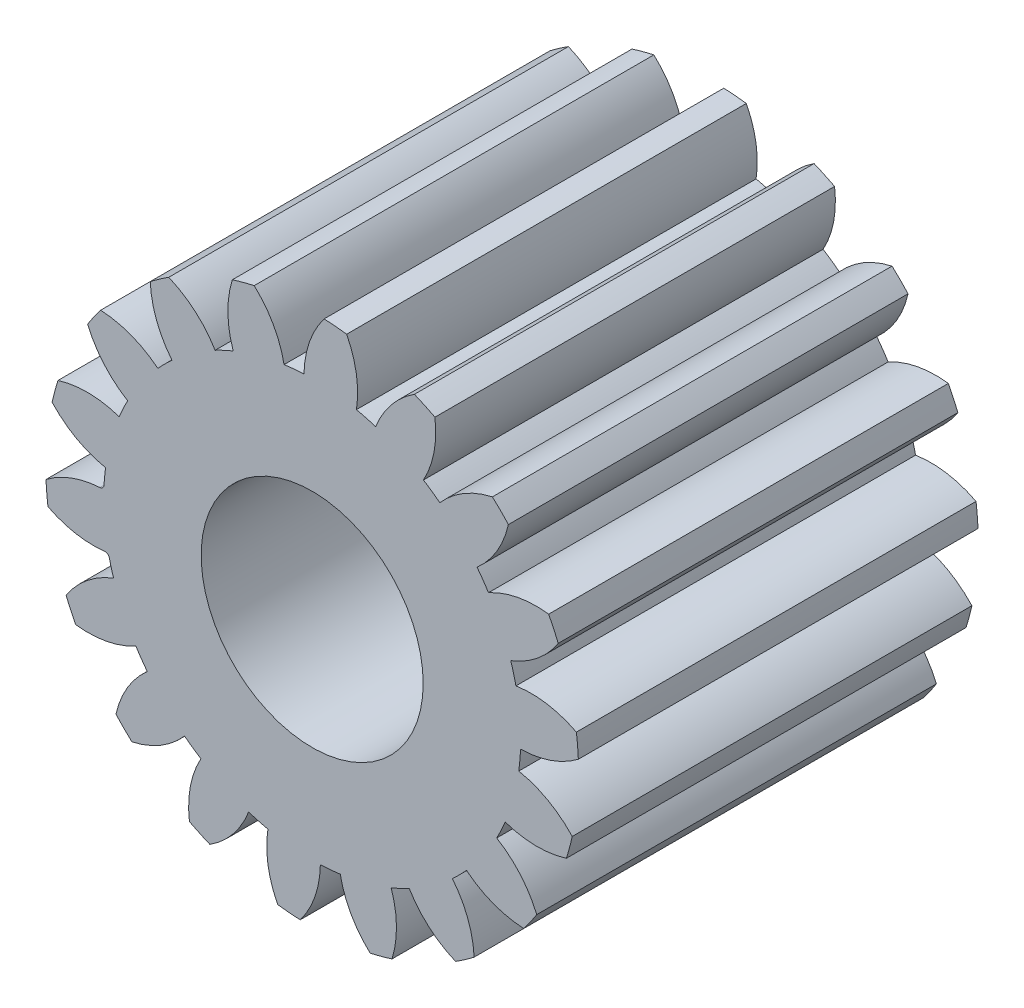
SolidWorks part; units mm, degrees
ref_plane "Front Plane" through (0, 0, 0) normal (0, 0, 1) x (1, 0, 0)
ref_plane "Top Plane" through (0, 0, 0) normal (0, 1, 0) x (1, 0, 0)
ref_plane "Right Plane" through (0, 0, 0) normal (1, 0, 0) x (0, 0, -1)
sketch "Sketch2" plane through (0, 0, 0) normal (0, 0, 1) x (1, 0, 0)
  line L0 (-27, 0) -> (-27, 24.0946)
  line L1 (-27, 0) -> (-17.5388, 25.9945)
  line L2 (-25.3717, 0) -> (-30, 0) construction
  line L3 (-25.3717, 0) -> (-27.6859, 0)
  line L4 (-27.6859, 0) -> (-30, 0)
  line L5 (-27.6859, 0) -> (-23.251, -10.1546) construction
  line L6 (-27.6859, 0) -> (-26.2076, -3.3849)
  line L7 (-26.2076, -3.3849) -> (-24.7293, -6.7697)
  line L8 (-24.7293, -6.7697) -> (-23.251, -10.1546)
  line L9 (-23.251, -10.1546) -> (-21.7727, -13.5394)
  line L10 (0, 0) -> (-29.8858, -2.6147) construction
  line L11 (0, 0) -> (-27.6859, 0) construction
  circle A0 centre (0, 0) radius 27
  circle A1 centre (0, 0) radius 23.4764
  circle A2 centre (0, 0) radius 30
  circle A3 centre (0, 0) radius 25.3717
  arc A4 (-29.9699, -1.3433) -> (-23.4582, 0.9243) centre (-23.251, -10.1546) cw
  arc A5 (-29.7479, -3.8814) -> (-22.9413, -4.9837) centre (-24.6611, 5.9628) ccw
  dimension "D1" = 54
  dimension "D2" = 60
  dimension "D3" = 46.9528
  dimension "D4" = 20
  dimension "D6" = 5
sketch "Sketch5" plane through (0, 0, 0) normal (0, 0, 1) x (1, 0, 0)
  arc A0 (-23.4582, 0.9243) -> (-29.9699, -1.3433) centre (-23.251, -10.1546) ccw construction
  arc A1 (-23.4582, 0.9243) -> (-29.9699, -1.3433) centre (-23.251, -10.1546) ccw
  arc A2 (-29.7479, -3.8814) -> (-22.9413, -4.9837) centre (-24.6611, 5.9628) ccw construction
  arc A3 (-29.7479, -3.8814) -> (-22.9413, -4.9837) centre (-24.6611, 5.9628) ccw
  circle A4 centre (0, 0) radius 23.4764 construction
  circle A5 centre (0, 0) radius 30 construction
  arc A6 (-23.4582, 0.9243) -> (-22.9413, -4.9837) centre (0, 0) ccw
  arc A7 (-29.9699, -1.3433) -> (-29.7479, -3.8814) centre (0, 0) ccw
extrude "Boss-Extrude3" add sketch "Sketch5" along normal blind 45
extrude "Boss-Extrude4" add sketch "Sketch2" along normal blind 45 contours A1
fillet "Fillet1" radius 0.5 1 edges at (-23.4582, 0.9243, 22.5)
fillet "Fillet3" radius 0.5 1 edges at (-22.9413, -4.9837, 22.5)
sketch "Sketch6" plane through (0, 0, 45) normal (0, 0, 1) x (1, 0, 0)
  circle A0 centre (0, 0) radius 12.5
  dimension "D1" = 25
pattern_circular "CirPattern1" count 18 over 360 about axis through (0, 0, 0) along (0, 0, 1) of "Boss-Extrude3"
extrude "Cut-Extrude1" cut sketch "Sketch6" against normal blind 45
equation "\"Teeth\" = 18"
equation "\"Module\"= 3"
equation "\"pcd\"= \"Teeth\" * \"Module\""
equation "\"circularpitch\"= 3.1415 * \"Module\""
equation "\"diametricalpitch\"= 1 / \"Module\""
equation "\"addendum\"= \"Module\""
equation "\"addendumCircularDiameter\"= \"pcd\" + 2 * \"Module\""
equation "\"clearance\"= \"circularpitch\" / \"Teeth\""
equation "\"dedendum\"= \"addendum\" + \"clearance\""
equation "\"dedendumCircularDiameter\"= \"pcd\" - 2 * \"dedendum\""
equation "\"pressureangle\"= 20"
equation "\"circularpitchangle\"= \"circularpitch\" * 360 / ( 3.1415 * \"pcd\" * 4 )"
equation "\"D2@Sketch2\"=\"addendumCircularDiameter\""
equation "\"D1@Sketch2\"=\"pcd\""
equation "\"D3@Sketch2\"=\"dedendumCircularDiameter\""
equation "\"D4@Sketch2\"=\"pressureangle\""
equation "\"D6@Sketch2\"=\"circularpitchangle\""
equation "\"D1@CirPattern1\"=\"Teeth\""
